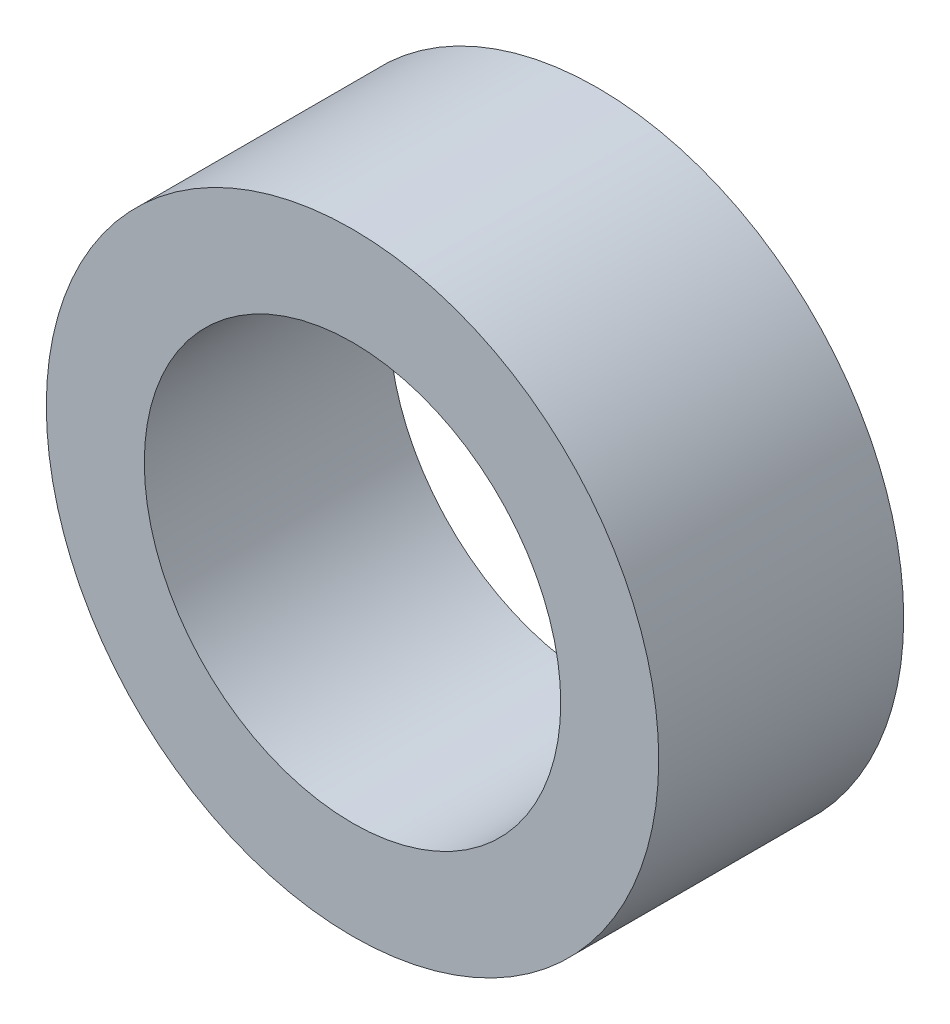
SolidWorks part; units mm, degrees
ref_plane "Front Plane" through (0, 0, 0) normal (1, 0, 0) x (0, 1, 0)
ref_plane "Top Plane" through (0, 0, 0) normal (0, 0, 1) x (0, 1, 0)
ref_plane "Right Plane" through (0, 0, 0) normal (0, 1, 0) x (-1, 0, 0)
sketch "Sketch1" plane through (0, 0, 0) normal (0, 0, 1) x (0, 1, 0)
  circle A0 centre (0, 0) radius 2.5
  dimension "D1" = 5
extrude "Boss-Extrude1" add sketch "Sketch1" along normal blind 2
sketch "Sketch2" plane through (0, 0, 2) normal (0, 0, 1) x (1, 0, 0)
  circle A0 centre (0, 0) radius 1.7
  dimension "D1" = 3.4
extrude "Cut-Extrude1" cut sketch "Sketch2" against normal through all both and the other way through all
